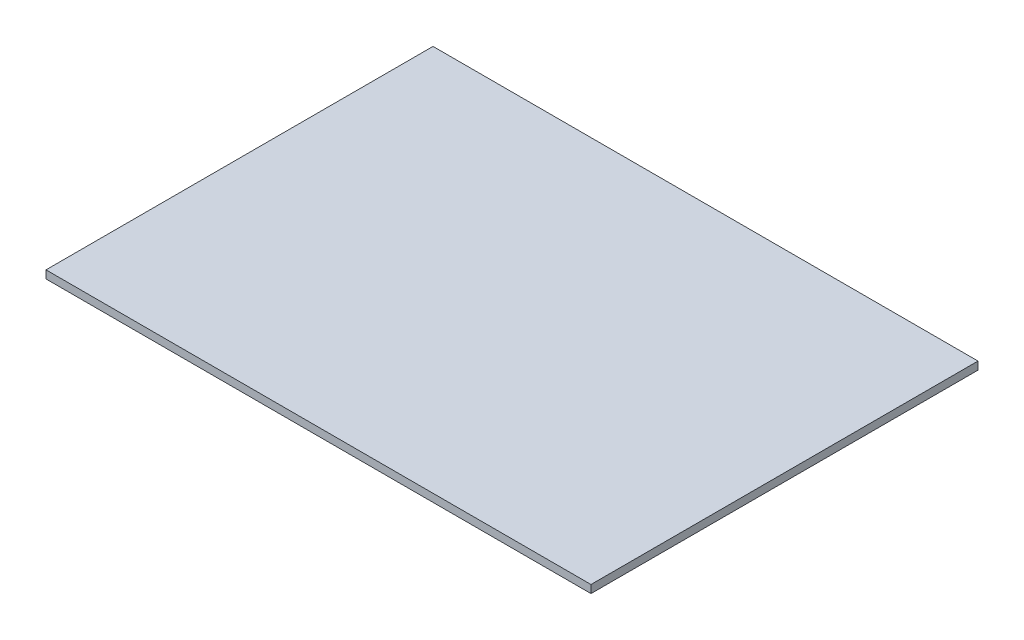
SolidWorks part; units mm, degrees
ref_plane "Front Plane" through (0, 0, 0) normal (0, 0, 1) x (1, 0, 0)
ref_plane "Top Plane" through (0, 0, 0) normal (0, 1, 0) x (1, 0, 0)
ref_plane "Right Plane" through (0, 0, 0) normal (1, 0, 0) x (0, 0, -1)
sketch "Sketch1" plane through (0, 0, 0) normal (0, 1, 0) x (1, 0, 0)
  line L1 (0, 0) -> (876.3, 0)
  line L2 (0, 0) -> (0, 622.3)
  line L3 (0, 622.3) -> (876.3, 622.3)
  line L4 (876.3, 0) -> (876.3, 622.3)
  dimension "D1" = 876.3
  dimension "D2" = 622.3
extrude "Boss-Extrude1" add sketch "Sketch1" along normal blind 12.7
